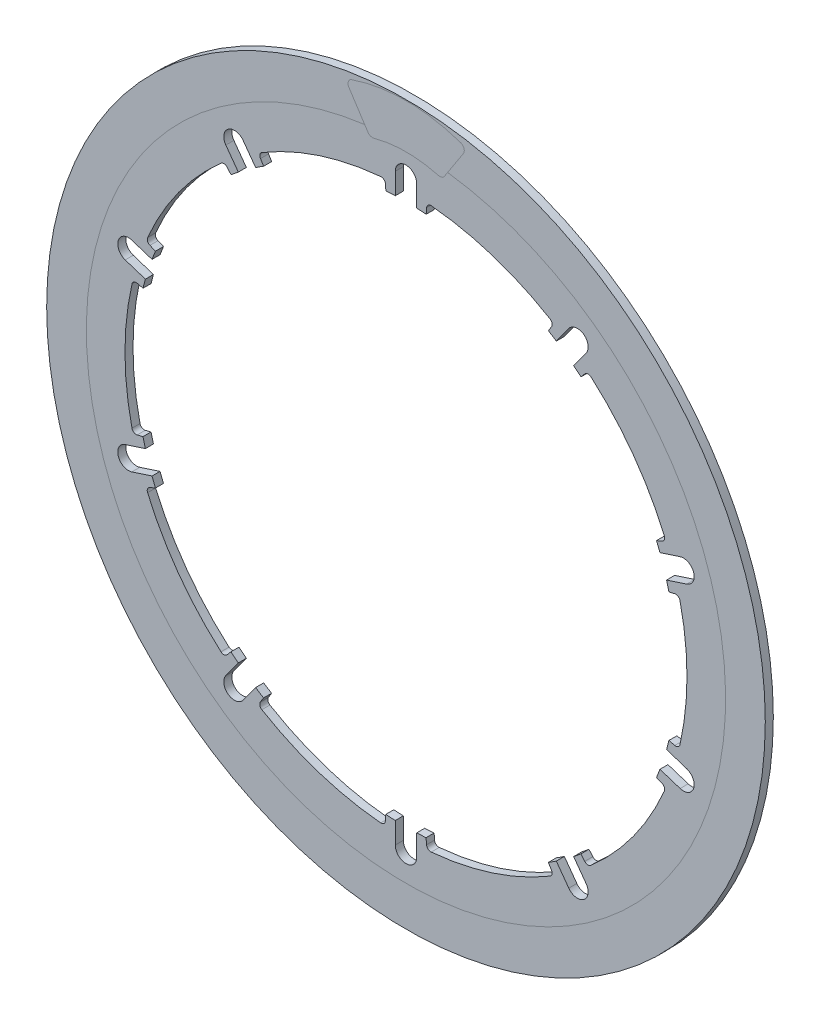
SolidWorks part; units mm, degrees
material "Gray Cast Iron"
ref_plane "Front Plane" through (0, 0, 0) normal (0, 0, 1) x (1, 0, 0)
ref_plane "Top Plane" through (0, 0, 0) normal (0, 1, 0) x (1, 0, 0)
ref_plane "Right Plane" through (0, 0, 0) normal (1, 0, 0) x (0, 0, -1)
sketch "Sketch1" plane through (0, 0, 0) normal (0, 0, 1) x (1, 0, 0)
  circle A0 centre (0, 0) radius 212.725
  dimension "D1" = 425.45
extrude "Boss-Extrude1" add sketch "Sketch1" along normal blind 4.7625
sketch3d "3DSketch3" [suppressed]
  line L4 (22.632, 184.3324, 30.7403) -> (33.9015, 201.686, 30.7403)
  line L5 (-33.9015, 201.686, 30.7403) -> (-22.632, 184.3324, 30.7403)
  arc A2 (-19.1346, 182.9983, 30.7403) -> (19.1346, 182.9983, 30.7403) centre (0, 112.7617, 30.7403) ccw
  spline S10 degree 3 poles (-22.632, 184.3324, 30.7403) (-22.5988, 184.2811, 30.7403) (-22.5293, 184.1805, 30.7403) (-22.4165, 184.0361, 30.7403) (-22.2957, 183.8983, 30.7403) (-22.1669, 183.7678, 30.7403) (-22.0309, 183.6449, 30.7403) (-21.8881, 183.53, 30.7403) (-21.7389, 183.4235, 30.7403) (-21.5838, 183.3258, 30.7403) (-21.4233, 183.2372, 30.7403) (-21.258, 183.1581, 30.7403) (-21.0428, 183.0698, 30.7403) (-20.7737, 182.9843, 30.7403) (-20.4488, 182.9172, 30.7403) (-20.1187, 182.8844, 30.7403) (-19.7871, 182.8865, 30.7403) (-19.4572, 182.9221, 30.7403) (-19.2411, 182.9691, 30.7403) (-19.1346, 182.9983, 30.7403) knots 0 0 0 0 0.045782 0.091558 0.137334 0.183113 0.228892 0.274672 0.32045 0.366227 0.412004 0.457782 0.503559 0.586301 0.669039 0.751777 0.834518 0.917255 1 1 1 1
  spline S11 degree 3 poles (19.1346, 182.9983, 30.7403) (19.1932, 182.9822, 30.7403) (19.3112, 182.9536, 30.7403) (19.4903, 182.9212, 30.7403) (19.6709, 182.8988, 30.7403) (19.8526, 182.8871, 30.7403) (20.0347, 182.8856, 30.7403) (20.2165, 182.8946, 30.7403) (20.3976, 182.9139, 30.7403) (20.5772, 182.9436, 30.7403) (20.7548, 182.9836, 30.7403) (20.9299, 183.0336, 30.7403) (21.1494, 183.1103, 30.7403) (21.4086, 183.2251, 30.7403) (21.6981, 183.3917, 30.7403) (21.9686, 183.5877, 30.7403) (22.2165, 183.8112, 30.7403) (22.4407, 184.059, 30.7403) (22.5716, 184.239, 30.7403) (22.632, 184.3324, 30.7403) knots 0 0 0 0 0.045473 0.090941 0.136409 0.181879 0.227351 0.272822 0.318291 0.36376 0.409229 0.454698 0.500168 0.583473 0.666777 0.750082 0.83339 0.916693 1 1 1 1
  spline S12 degree 3 poles (33.9015, 201.686, 30.7403) (33.9344, 201.7364, 30.7403) (33.9971, 201.839, 30.7403) (34.0817, 201.9976, 30.7403) (34.1575, 202.1609, 30.7403) (34.2237, 202.3283, 30.7403) (34.2804, 202.4992, 30.7403) (34.3274, 202.6731, 30.7403) (34.3646, 202.8492, 30.7403) (34.3917, 203.0273, 30.7403) (34.4086, 203.2065, 30.7403) (34.4153, 203.3864, 30.7403) (34.4119, 203.5665, 30.7403) (34.3756, 204.0435, 30.7403) (34.1614, 204.8075, 30.7403) (33.6821, 205.4852, 30.7403) (33.2752, 205.8566, 30.7403) (33.0454, 206.0314, 30.7403) (32.8006, 206.1843, 30.7403) (32.5436, 206.3149, 30.7403) (32.3643, 206.3858, 30.7403) (32.2732, 206.417, 30.7403) knots 0 0 0 0 0.031297 0.062588 0.093878 0.12517 0.156463 0.187756 0.219048 0.250339 0.28163 0.312921 0.344212 0.375504 0.562427 0.749344 0.799474 0.849606 0.899737 0.949865 1 1 1 1
  spline S13 degree 3 poles (32.2732, 206.417, 30.7403) (31.9592, 206.5252, 30.7403) (31.3303, 206.7384, 30.7403) (30.3838, 207.0486, 30.7403) (29.4343, 207.3495, 30.7403) (28.4817, 207.6406, 30.7403) (27.5262, 207.9222, 30.7403) (26.568, 208.1942, 30.7403) (25.6071, 208.4564, 30.7403) (24.6436, 208.7091, 30.7403) (23.6776, 208.952, 30.7403) (22.7092, 209.1852, 30.7403) (21.7385, 209.4087, 30.7403) (20.7656, 209.6224, 30.7403) (19.7906, 209.8263, 30.7403) (18.8136, 210.0204, 30.7403) (17.8348, 210.2046, 30.7403) (16.8541, 210.3791, 30.7403) (15.8717, 210.5436, 30.7403) (14.8877, 210.6982, 30.7403) (13.9022, 210.843, 30.7403) (12.9153, 210.9778, 30.7403) (11.927, 211.1027, 30.7403) (9.4532, 211.3901, 30.7403) (5.4798, 211.7206, 30.7403) (0, 211.8722, 30.7403) (-5.4798, 211.7206, 30.7403) (-9.7842, 211.3626, 30.7403) (-12.9159, 210.9828, 30.7403) (-14.8884, 210.7032, 30.7403) (-16.8549, 210.384, 30.7403) (-18.8146, 210.0253, 30.7403) (-20.7667, 209.6273, 30.7403) (-22.7103, 209.1901, 30.7403) (-24.6448, 208.7139, 30.7403) (-26.5694, 208.1991, 30.7403) (-28.483, 207.645, 30.7403) (-30.3853, 207.0535, 30.7403) (-31.6453, 206.6334, 30.7403) (-32.2732, 206.417, 30.7403) knots 0 0 0 0 0.015151 0.030302 0.045452 0.060603 0.075754 0.090905 0.106056 0.121206 0.136357 0.151508 0.166659 0.18181 0.19696 0.212111 0.227262 0.242413 0.257563 0.272714 0.287865 0.303016 0.318167 0.333317 0.41666 0.500002 0.583344 0.666687 0.696988 0.727289 0.75759 0.787892 0.818193 0.848494 0.878795 0.909096 0.939398 0.969699 1 1 1 1
  spline S14 degree 3 poles (-32.2732, 206.417, 30.7403) (-32.33, 206.3976, 30.7403) (-32.4424, 206.3554, 30.7403) (-32.6063, 206.2826, 30.7403) (-32.7663, 206.2007, 30.7403) (-32.9213, 206.1097, 30.7403) (-33.071, 206.0102, 30.7403) (-33.2148, 205.9024, 30.7403) (-33.3523, 205.7867, 30.7403) (-33.4831, 205.6634, 30.7403) (-33.6067, 205.5329, 30.7403) (-33.7226, 205.3956, 30.7403) (-33.8307, 205.2519, 30.7403) (-34.0967, 204.8533, 30.7403) (-34.3994, 204.1174, 30.7403) (-34.4385, 203.2861, 30.7403) (-34.346, 202.7423, 30.7403) (-34.2724, 202.4636, 30.7403) (-34.1736, 202.193, 30.7403) (-34.0515, 201.9325, 30.7403) (-33.9541, 201.7665, 30.7403) (-33.9015, 201.686, 30.7403) knots 0 0 0 0 0.031241 0.062476 0.093711 0.124947 0.156184 0.187421 0.218658 0.249893 0.281128 0.312363 0.343599 0.374835 0.562326 0.749809 0.799846 0.849885 0.899924 0.949958 1 1 1 1
  point P8 (0, 112.7617, -42.0561)
sketch "Sketch4" plane through (0, 0, 4.7625) normal (0, 0, 1) x (1, 0, 0)
  line L2 (22.7365, 184.6731) -> (34.006, 202.0267)
  line L3 (-33.7971, 202.0267) -> (-22.5275, 184.6731)
  arc A1 (19.2391, 183.339) -> (-19.0302, 183.339) centre (0.1045, 113.1023) ccw
  spline S5 degree 3 poles (34.006, 202.0267) (34.0389, 202.0771) (34.1016, 202.1797) (34.1862, 202.3383) (34.262, 202.5016) (34.3282, 202.669) (34.4038, 202.8969) (34.46, 203.1306) (34.4962, 203.3679) (34.5131, 203.5472) (34.5198, 203.7271) (34.5163, 203.9072) (34.4801, 204.3842) (34.2659, 205.1481) (33.7866, 205.8259) (33.3797, 206.1973) (33.1498, 206.3721) (32.9051, 206.525) (32.648, 206.6556) (32.4688, 206.7265) (32.3776, 206.7577) knots 0 0 0 0 0.031297 0.062588 0.093878 0.12517 0.156463 0.219048 0.250339 0.28163 0.312921 0.344212 0.375504 0.562427 0.749344 0.799474 0.849606 0.899737 0.949865 1 1 1 1
  spline S6 degree 3 poles (19.2391, 183.339) (19.2977, 183.3229) (19.4156, 183.2943) (19.5948, 183.2619) (19.7754, 183.2395) (19.9571, 183.2278) (20.1392, 183.2263) (20.321, 183.2353) (20.5021, 183.2546) (20.7416, 183.2942) (20.9771, 183.3543) (21.2539, 183.451) (21.5131, 183.5658) (21.8026, 183.7323) (22.073, 183.9284) (22.321, 184.1519) (22.5452, 184.3996) (22.6761, 184.5797) (22.7365, 184.6731) knots 0 0 0 0 0.045473 0.090941 0.136409 0.181879 0.227351 0.272822 0.318291 0.36376 0.454698 0.500168 0.583473 0.666777 0.750082 0.83339 0.916693 1 1 1 1
  spline S7 degree 3 poles (-22.5275, 184.6731) (-22.4943, 184.6218) (-22.4249, 184.5212) (-22.312, 184.3768) (-22.1912, 184.239) (-22.0624, 184.1085) (-21.9264, 183.9856) (-21.7836, 183.8707) (-21.6344, 183.7642) (-21.4276, 183.6339) (-21.2101, 183.5219) (-20.9383, 183.4105) (-20.6692, 183.325) (-20.3444, 183.2579) (-20.0142, 183.225) (-19.6827, 183.2272) (-19.3527, 183.2628) (-19.1367, 183.3098) (-19.0302, 183.339) knots 0 0 0 0 0.045782 0.091558 0.137334 0.183113 0.228892 0.274672 0.32045 0.366227 0.457782 0.503559 0.586301 0.669039 0.751777 0.834518 0.917255 1 1 1 1
  spline S8 degree 3 poles (-32.1687, 206.7577) (-32.2255, 206.7383) (-32.3379, 206.6961) (-32.5019, 206.6233) (-32.6618, 206.5414) (-32.8168, 206.4504) (-33.0164, 206.3177) (-33.2043, 206.1685) (-33.3786, 206.0041) (-33.5022, 205.8736) (-33.6182, 205.7363) (-33.7262, 205.5926) (-33.9922, 205.194) (-34.2949, 204.4581) (-34.3341, 203.6268) (-34.2415, 203.083) (-34.1679, 202.8043) (-34.0691, 202.5337) (-33.947, 202.2732) (-33.8496, 202.1072) (-33.7971, 202.0267) knots 0 0 0 0 0.031241 0.062476 0.093711 0.124947 0.156184 0.218658 0.249893 0.281128 0.312363 0.343599 0.374835 0.562326 0.749809 0.799846 0.849885 0.899924 0.949958 1 1 1 1
  spline S9 degree 3 poles (32.3776, 206.7577) (32.0637, 206.8659) (31.4348, 207.0791) (30.4883, 207.3893) (29.5388, 207.6902) (28.5862, 207.9813) (26.9938, 208.4506) (23.7904, 209.325) (20.2255, 210.1269) (16.6328, 210.7845) (14.6646, 211.0938) (13.0197, 211.3185) (12.0315, 211.4434) (9.5577, 211.7308) (5.5843, 212.0613) (0.1045, 212.2129) (-5.3753, 212.0613) (-9.6798, 211.7033) (-12.8114, 211.3235) (-14.7839, 211.0439) (-16.7504, 210.7247) (-18.7101, 210.366) (-20.6622, 209.968) (-22.6058, 209.5308) (-24.5403, 209.0546) (-26.4649, 208.5398) (-28.3785, 207.9857) (-30.2808, 207.3942) (-31.5409, 206.9741) (-32.1687, 206.7577) knots 0 0 0 0 0.015151 0.030302 0.045452 0.060603 0.075754 0.121206 0.212111 0.242413 0.287865 0.303016 0.318167 0.333317 0.41666 0.500002 0.583344 0.666687 0.696988 0.727289 0.75759 0.787892 0.818193 0.848494 0.878795 0.909096 0.939398 0.969699 1 1 1 1
sketch "Sketch8" plane through (0, 0, 0) normal (0, 0, -1) x (-1, 0, 0)
  circle A0 centre (0, 0) radius 166.37
  dimension "D1" = 332.74
extrude "Cut-Extrude1" cut sketch "Sketch8" against normal up to surface (4.7625 mm away) up to face at (212.725, 0, 4.7625)
sketch "Sketch9" plane through (0, 0, 0) normal (0, 0, -1) x (-1, 0, 0)
  line L1 (-6.35, 160.02) -> (6.35, 160.02)
  line L2 (-6.35, 160.02) -> (-6.35, 172.72)
  line L3 (-6.35, 172.72) -> (6.35, 172.72)
  line L4 (6.35, 160.02) -> (6.35, 172.72)
  line L5 (-6.35, 160.02) -> (6.35, 172.72) construction
  line L6 (-6.35, 172.72) -> (6.35, 160.02) construction
  circle A0 centre (0, 0) radius 166.37 construction
  circle A1 centre (0, 172.72) radius 6.35
  point P0 (0, 166.37)
  circle M4 centre (0, 0) radius 166.37
  dimension "D1" = 12.7
  dimension "D2" = 12.7
extrude "Cut-Extrude3" cut sketch "Sketch9" along direction (0, 0, 1) on the side against the normal up to surface (4.7625 mm away) contours L3 A1 | L3 A1 | A1 L4 M4 | A1 L2 M4
pattern_circular "CirPattern1" count 10 every 36 about axis through (0, 0, 0) along (0, 0, 1) of "Cut-Extrude3"
sketch "Sketch11" plane through (0, 0, 4.7625) normal (0, 0, 1) x (1, 0, 0)
  line L0 (-11.8938, 159.8321) -> (-12.1576, 163.3594)
  line L1 (-6.35, 166.2488) -> (-6.35, 160.1482)
  line L2 (6.35, 160.1482) -> (6.35, 166.2488)
  line L3 (11.9607, 159.8271) -> (12.2246, 163.3535)
  line L4 (6.35, 166.2488) -> (6.35, 172.72) construction
  arc A0 (11.9607, 159.8271) -> (6.35, 160.1482) centre (0, 0) ccw
  arc A1 (-6.35, 166.2488) -> (-92.5813, 138.2305) centre (0, 0) ccw construction
  arc A2 (92.5813, 138.2305) -> (6.35, 166.2488) centre (0, 0) ccw construction
  arc A3 (-6.35, 160.1482) -> (-11.8938, 159.8321) centre (0, 0) ccw
  arc A4 (-14.9183, 165.6998) -> (-92.5813, 138.2305) centre (0, 0) ccw
  arc A5 (92.5813, 138.2305) -> (14.9864, 165.6937) centre (0, 0) ccw
  arc A6 (-14.9183, 165.6998) -> (-12.1576, 163.3594) centre (-14.6905, 163.17) cw
  arc A7 (14.9864, 165.6937) -> (12.2246, 163.3535) centre (14.7576, 163.164) ccw
  arc M5 (-92.5813, 138.2305) -> (-6.35, 166.2488) centre (0, 0) cw
  arc M9 (6.35, 166.2488) -> (92.5813, 138.2305) centre (0, 0) cw
  dimension "D2" = 2.54
  dimension "D3" = 2.54
extrude "Boss-Extrude2" add sketch "Sketch11" against normal up to surface (4.7625 mm away) contours A0 L3 L2 M9 | A3 L1 L0 M5 up to face at (0, 0, 0)
pattern_circular "CirPattern2" count 10 every 36 about axis through (0, 0, 0) along (0, 0, 1) of "Boss-Extrude2"
sketch "Sketch15" [suppressed] plane through (0, 0, 6.35) normal (0, 0, 1) x (1, 0, 0)
  line L0 (-12.2165, 163.3739) -> (12.2261, 163.3732)
sketch "Sketch17" [suppressed] plane through (0, 0, 6.35) normal (0, 0, 1) x (1, 0, 0)
  line L0 (0, 0) -> (110.7699, 130.7089)
  line L1 (0, 0) -> (158.5451, 64.9479)
  arc A0 (161.9209, 73.4471) -> (119.8963, 131.2925) centre (0, 0) ccw
  arc A1 (161.9209, 73.4471) -> (158.5451, 64.9479) centre (156.138, 70.824) cw
  arc A2 (110.7699, 130.7089) -> (119.8963, 131.2925) centre (115.6143, 126.6035) cw
  dimension "D1" = 0
  dimension "D3" = 6.35
  dimension "D4" = 6.35
  dimension "D2" = 0
sketch "Sketch18" plane through (0, 0, 0) normal (0, 0, -1) x (-1, 0, 0)
  line L0 (33.7971, 202.0267) -> (22.5275, 184.6731) construction
  line L1 (-22.7365, 184.6731) -> (-34.006, 202.0267) construction
  line L2 (33.7971, 202.0267) -> (22.5275, 184.6731)
  line L3 (-22.7365, 184.6731) -> (-34.006, 202.0267)
  arc A0 (-24.6449, 187.6118) -> (24.4523, 187.637) centre (0, 0) ccw
  circle A1 centre (0, 0) radius 215.3351
  arc A2 (19.0302, 183.339) -> (-19.2391, 183.339) centre (-0.1045, 113.1023) ccw construction
  arc A3 (19.0302, 183.339) -> (-19.2391, 183.339) centre (-0.1045, 113.1023) ccw
  spline S0 degree 3 poles (-1450.1633, -1164.7301) (-59.0763, 285.4864) (32.2795, 197.129) (22.312, 184.3768) (22.1912, 184.239) (22.0624, 184.1085) (21.9264, 183.9856) (21.7836, 183.8707) (21.6344, 183.7642) (21.4276, 183.6339) (21.2101, 183.5219) (20.9383, 183.4105) (20.6692, 183.325) (20.3444, 183.2579) (20.0142, 183.225) (19.6827, 183.2272) (2.7527, 185.055) (8.5785, 322.4741) (2007.8128, 363.0309) knots -11.991769 -11.991769 -11.991769 -11.991769 0.045782 0.091558 0.137334 0.183113 0.228892 0.274672 0.32045 0.366227 0.457782 0.503559 0.586301 0.669039 0.751777 0.834518 0.917255 13.489507 13.489507 13.489507 13.489507 only from (22.5275, 184.6731) to (19.0302, 183.339) construction
  spline S1 degree 3 poles (-2016.3209, 153.4131) (-13.1774, 313.7756) (-3.6105, 186.1555) (-19.5948, 183.2619) (-19.7754, 183.2395) (-19.9571, 183.2278) (-20.1392, 183.2263) (-20.321, 183.2353) (-20.5021, 183.2546) (-20.7416, 183.2942) (-20.9771, 183.3543) (-21.2539, 183.451) (-21.5131, 183.5658) (-21.8026, 183.7323) (-22.073, 183.9284) (-22.321, 184.1519) (-33.7349, 196.7661) (61.8944, 295.2324) (1583.0626, -1002.353) knots -12.036429 -12.036429 -12.036429 -12.036429 0.045473 0.090941 0.136409 0.181879 0.227351 0.272822 0.318291 0.36376 0.454698 0.500168 0.583473 0.666777 0.750082 0.83339 0.916693 13.47468 13.47468 13.47468 13.47468 only from (-19.2391, 183.339) to (-22.7365, 184.6731) construction
  spline S2 degree 3 poles (-741.6985, 2071.3636) (51.5513, 215.3428) (-28.083, 190.8965) (-34.1862, 202.3383) (-34.262, 202.5016) (-34.3282, 202.669) (-34.4038, 202.8969) (-34.46, 203.1306) (-34.4962, 203.3679) (-34.5131, 203.5472) (-34.5198, 203.7271) (-34.5163, 203.9072) (-34.4801, 204.3842) (-34.2659, 205.1481) (-33.7866, 205.8259) (-33.3797, 206.1973) (-33.1498, 206.3721) (-32.9051, 206.525) (-19.4783, 213.3465) (41.9008, 122.514) (-1615.5521, -1012.0405) knots -6.679954 -6.679954 -6.679954 -6.679954 0.031297 0.062588 0.093878 0.12517 0.156463 0.219048 0.250339 0.28163 0.312921 0.344212 0.375504 0.562427 0.749344 0.799474 0.849606 0.899737 0.949865 8.706653 8.706653 8.706653 8.706653 only from (-34.006, 202.0267) to (-32.3776, 206.7577) construction
  spline S3 degree 3 poles (1661.243, 1259.3746) (-203.7859, -162.5293) (-163.0238, 163.9576) (-30.4883, 207.3893) (-29.5388, 207.6902) (-28.5862, 207.9813) (-26.9938, 208.4506) (-23.7904, 209.325) (-20.2255, 210.1269) (-16.6328, 210.7845) (-14.6646, 211.0938) (-13.0197, 211.3185) (-12.0315, 211.4434) (-9.5577, 211.7308) (-5.5843, 212.0613) (-0.1045, 212.2129) (5.3753, 212.0613) (9.6798, 211.7033) (12.8114, 211.3235) (14.7839, 211.0439) (16.7504, 210.7247) (18.7101, 210.366) (20.6622, 209.968) (22.6058, 209.5308) (24.5403, 209.0546) (26.4649, 208.5398) (28.3785, 207.9857) (189.3327, 157.9434) (218.1983, -304.2931) (-1891.4217, 643.6889) knots -6.319065 -6.319065 -6.319065 -6.319065 0.015151 0.030302 0.045452 0.060603 0.075754 0.121206 0.212111 0.242413 0.287865 0.303016 0.318167 0.333317 0.41666 0.500002 0.583344 0.666687 0.696988 0.727289 0.75759 0.787892 0.818193 0.848494 0.878795 0.909096 0.939398 0.969699 8.600273 8.600273 8.600273 8.600273 only from (-32.3776, 206.7577) to (32.1687, 206.7577) construction
  spline S4 degree 3 poles (1741.3262, -829.6052) (-26.9574, 143.7974) (20.6648, 211.8759) (32.5019, 206.6233) (32.6618, 206.5414) (32.8168, 206.4504) (33.0164, 206.3177) (33.2043, 206.1685) (33.3786, 206.0041) (33.5022, 205.8736) (33.6182, 205.7363) (33.7262, 205.5926) (33.9922, 205.194) (34.2949, 204.4581) (34.3341, 203.6268) (34.2415, 203.083) (34.1679, 202.8043) (34.0691, 202.5337) (27.687, 188.9067) (-76.4304, 222.6453) (533.1826, 2136.6237) knots -6.671073 -6.671073 -6.671073 -6.671073 0.031241 0.062476 0.093711 0.124947 0.156184 0.218658 0.249893 0.281128 0.312363 0.343599 0.374835 0.562326 0.749809 0.799846 0.849885 0.899924 0.949958 8.70048 8.70048 8.70048 8.70048 only from (32.1687, 206.7577) to (33.7971, 202.0267) construction
  spline S5 degree 3 poles (22.5275, 184.6731) (22.4943, 184.6218) (22.4249, 184.5212) (22.312, 184.3768) (22.1912, 184.239) (22.0624, 184.1085) (21.9264, 183.9856) (21.7836, 183.8707) (21.6344, 183.7642) (21.4276, 183.6339) (21.2101, 183.5219) (20.9383, 183.4105) (20.6692, 183.325) (20.3444, 183.2579) (20.0142, 183.225) (19.6827, 183.2272) (19.3527, 183.2628) (19.1367, 183.3098) (19.0302, 183.339) knots 0 0 0 0 0.045782 0.091558 0.137334 0.183113 0.228892 0.274672 0.32045 0.366227 0.457782 0.503559 0.586301 0.669039 0.751777 0.834518 0.917255 1 1 1 1
  spline S6 degree 3 poles (-19.2391, 183.339) (-19.2977, 183.3229) (-19.4156, 183.2943) (-19.5948, 183.2619) (-19.7754, 183.2395) (-19.9571, 183.2278) (-20.1392, 183.2263) (-20.321, 183.2353) (-20.5021, 183.2546) (-20.7416, 183.2942) (-20.9771, 183.3543) (-21.2539, 183.451) (-21.5131, 183.5658) (-21.8026, 183.7323) (-22.073, 183.9284) (-22.321, 184.1519) (-22.5452, 184.3996) (-22.6761, 184.5797) (-22.7365, 184.6731) knots 0 0 0 0 0.045473 0.090941 0.136409 0.181879 0.227351 0.272822 0.318291 0.36376 0.454698 0.500168 0.583473 0.666777 0.750082 0.83339 0.916693 1 1 1 1
  spline S7 degree 3 poles (-34.006, 202.0267) (-34.0389, 202.0771) (-34.1016, 202.1797) (-34.1862, 202.3383) (-34.262, 202.5016) (-34.3282, 202.669) (-34.4038, 202.8969) (-34.46, 203.1306) (-34.4962, 203.3679) (-34.5131, 203.5472) (-34.5198, 203.7271) (-34.5163, 203.9072) (-34.4801, 204.3842) (-34.2659, 205.1481) (-33.7866, 205.8259) (-33.3797, 206.1973) (-33.1498, 206.3721) (-32.9051, 206.525) (-32.648, 206.6556) (-32.4688, 206.7265) (-32.3776, 206.7577) knots 0 0 0 0 0.031297 0.062588 0.093878 0.12517 0.156463 0.219048 0.250339 0.28163 0.312921 0.344212 0.375504 0.562427 0.749344 0.799474 0.849606 0.899737 0.949865 1 1 1 1
  spline S8 degree 3 poles (-32.3776, 206.7577) (-32.0637, 206.8659) (-31.4348, 207.0791) (-30.4883, 207.3893) (-29.5388, 207.6902) (-28.5862, 207.9813) (-26.9938, 208.4506) (-23.7904, 209.325) (-20.2255, 210.1269) (-16.6328, 210.7845) (-14.6646, 211.0938) (-13.0197, 211.3185) (-12.0315, 211.4434) (-9.5577, 211.7308) (-5.5843, 212.0613) (-0.1045, 212.2129) (5.3753, 212.0613) (9.6798, 211.7033) (12.8114, 211.3235) (14.7839, 211.0439) (16.7504, 210.7247) (18.7101, 210.366) (20.6622, 209.968) (22.6058, 209.5308) (24.5403, 209.0546) (26.4649, 208.5398) (28.3785, 207.9857) (30.2808, 207.3942) (31.5409, 206.9741) (32.1687, 206.7577) knots 0 0 0 0 0.015151 0.030302 0.045452 0.060603 0.075754 0.121206 0.212111 0.242413 0.287865 0.303016 0.318167 0.333317 0.41666 0.500002 0.583344 0.666687 0.696988 0.727289 0.75759 0.787892 0.818193 0.848494 0.878795 0.909096 0.939398 0.969699 1 1 1 1
  spline S9 degree 3 poles (32.1687, 206.7577) (32.2255, 206.7383) (32.3379, 206.6961) (32.5019, 206.6233) (32.6618, 206.5414) (32.8168, 206.4504) (33.0164, 206.3177) (33.2043, 206.1685) (33.3786, 206.0041) (33.5022, 205.8736) (33.6182, 205.7363) (33.7262, 205.5926) (33.9922, 205.194) (34.2949, 204.4581) (34.3341, 203.6268) (34.2415, 203.083) (34.1679, 202.8043) (34.0691, 202.5337) (33.947, 202.2732) (33.8496, 202.1072) (33.7971, 202.0267) knots 0 0 0 0 0.031241 0.062476 0.093711 0.124947 0.156184 0.218658 0.249893 0.281128 0.312363 0.343599 0.374835 0.562326 0.749809 0.799846 0.849885 0.899924 0.949958 1 1 1 1
  dimension "D1" = 378.4471
  dimension "D2" = 430.6702
split line "Split Line3"
sketch "Sketch19" plane through (0, 0, 6.35) normal (0, 0, 1) x (1, 0, 0)
  line L0 (-33.7971, 202.0267) -> (-22.5275, 184.6731) construction
  line L1 (22.7365, 184.6731) -> (34.006, 202.0267) construction
  line L2 (-33.7971, 202.0267) -> (-22.5275, 184.6731)
  line L3 (22.7365, 184.6731) -> (34.006, 202.0267)
  arc A0 (-24.4523, 187.637) -> (24.6449, 187.6118) centre (0, 0) ccw
  circle A1 centre (0, 0) radius 215.3351
  arc A2 (19.2391, 183.339) -> (-19.0302, 183.339) centre (0.1045, 113.1023) ccw construction
  arc A3 (19.2391, 183.339) -> (-19.0302, 183.339) centre (0.1045, 113.1023) ccw
  spline S0 degree 3 poles (1450.1633, -1164.7301) (59.0763, 285.4864) (-32.2795, 197.129) (-22.312, 184.3768) (-22.1912, 184.239) (-22.0624, 184.1085) (-21.9264, 183.9856) (-21.7836, 183.8707) (-21.6344, 183.7642) (-21.4276, 183.6339) (-21.2101, 183.5219) (-20.9383, 183.4105) (-20.6692, 183.325) (-20.3444, 183.2579) (-20.0142, 183.225) (-19.6827, 183.2272) (-2.7527, 185.055) (-8.5785, 322.4741) (-2007.8128, 363.0309) knots -11.991769 -11.991769 -11.991769 -11.991769 0.045782 0.091558 0.137334 0.183113 0.228892 0.274672 0.32045 0.366227 0.457782 0.503559 0.586301 0.669039 0.751777 0.834518 0.917255 13.489507 13.489507 13.489507 13.489507 only from (-22.5275, 184.6731) to (-19.0302, 183.339) construction
  spline S1 degree 3 poles (-1741.3262, -829.6052) (26.9574, 143.7974) (-20.6648, 211.8759) (-32.5019, 206.6233) (-32.6618, 206.5414) (-32.8168, 206.4504) (-33.0164, 206.3177) (-33.2043, 206.1685) (-33.3786, 206.0041) (-33.5022, 205.8736) (-33.6182, 205.7363) (-33.7262, 205.5926) (-33.9922, 205.194) (-34.2949, 204.4581) (-34.3341, 203.6268) (-34.2415, 203.083) (-34.1679, 202.8043) (-34.0691, 202.5337) (-27.687, 188.9067) (76.4304, 222.6453) (-533.1826, 2136.6237) knots -6.671073 -6.671073 -6.671073 -6.671073 0.031241 0.062476 0.093711 0.124947 0.156184 0.218658 0.249893 0.281128 0.312363 0.343599 0.374835 0.562326 0.749809 0.799846 0.849885 0.899924 0.949958 8.70048 8.70048 8.70048 8.70048 only from (-32.1687, 206.7577) to (-33.7971, 202.0267) construction
  spline S2 degree 3 poles (-1661.243, 1259.3746) (203.7859, -162.5293) (163.0238, 163.9576) (30.4883, 207.3893) (29.5388, 207.6902) (28.5862, 207.9813) (26.9938, 208.4506) (23.7904, 209.325) (20.2255, 210.1269) (16.6328, 210.7845) (14.6646, 211.0938) (13.0197, 211.3185) (12.0315, 211.4434) (9.5577, 211.7308) (5.5843, 212.0613) (0.1045, 212.2129) (-5.3753, 212.0613) (-9.6798, 211.7033) (-12.8114, 211.3235) (-14.7839, 211.0439) (-16.7504, 210.7247) (-18.7101, 210.366) (-20.6622, 209.968) (-22.6058, 209.5308) (-24.5403, 209.0546) (-26.4649, 208.5398) (-28.3785, 207.9857) (-189.3327, 157.9434) (-218.1983, -304.2931) (1891.4217, 643.6889) knots -6.319065 -6.319065 -6.319065 -6.319065 0.015151 0.030302 0.045452 0.060603 0.075754 0.121206 0.212111 0.242413 0.287865 0.303016 0.318167 0.333317 0.41666 0.500002 0.583344 0.666687 0.696988 0.727289 0.75759 0.787892 0.818193 0.848494 0.878795 0.909096 0.939398 0.969699 8.600273 8.600273 8.600273 8.600273 only from (32.3776, 206.7577) to (-32.1687, 206.7577) construction
  spline S3 degree 3 poles (741.6985, 2071.3636) (-51.5513, 215.3428) (28.083, 190.8965) (34.1862, 202.3383) (34.262, 202.5016) (34.3282, 202.669) (34.4038, 202.8969) (34.46, 203.1306) (34.4962, 203.3679) (34.5131, 203.5472) (34.5198, 203.7271) (34.5163, 203.9072) (34.4801, 204.3842) (34.2659, 205.1481) (33.7866, 205.8259) (33.3797, 206.1973) (33.1498, 206.3721) (32.9051, 206.525) (19.4783, 213.3465) (-41.9008, 122.514) (1615.5521, -1012.0405) knots -6.679954 -6.679954 -6.679954 -6.679954 0.031297 0.062588 0.093878 0.12517 0.156463 0.219048 0.250339 0.28163 0.312921 0.344212 0.375504 0.562427 0.749344 0.799474 0.849606 0.899737 0.949865 8.706653 8.706653 8.706653 8.706653 only from (34.006, 202.0267) to (32.3776, 206.7577) construction
  spline S4 degree 3 poles (2016.3209, 153.4131) (13.1774, 313.7756) (3.6105, 186.1555) (19.5948, 183.2619) (19.7754, 183.2395) (19.9571, 183.2278) (20.1392, 183.2263) (20.321, 183.2353) (20.5021, 183.2546) (20.7416, 183.2942) (20.9771, 183.3543) (21.2539, 183.451) (21.5131, 183.5658) (21.8026, 183.7323) (22.073, 183.9284) (22.321, 184.1519) (33.7349, 196.7661) (-61.8944, 295.2324) (-1583.0626, -1002.353) knots -12.036429 -12.036429 -12.036429 -12.036429 0.045473 0.090941 0.136409 0.181879 0.227351 0.272822 0.318291 0.36376 0.454698 0.500168 0.583473 0.666777 0.750082 0.83339 0.916693 13.47468 13.47468 13.47468 13.47468 only from (19.2391, 183.339) to (22.7365, 184.6731) construction
  spline S5 degree 3 poles (-22.5275, 184.6731) (-22.4943, 184.6218) (-22.4249, 184.5212) (-22.312, 184.3768) (-22.1912, 184.239) (-22.0624, 184.1085) (-21.9264, 183.9856) (-21.7836, 183.8707) (-21.6344, 183.7642) (-21.4276, 183.6339) (-21.2101, 183.5219) (-20.9383, 183.4105) (-20.6692, 183.325) (-20.3444, 183.2579) (-20.0142, 183.225) (-19.6827, 183.2272) (-19.3527, 183.2628) (-19.1367, 183.3098) (-19.0302, 183.339) knots 0 0 0 0 0.045782 0.091558 0.137334 0.183113 0.228892 0.274672 0.32045 0.366227 0.457782 0.503559 0.586301 0.669039 0.751777 0.834518 0.917255 1 1 1 1
  spline S6 degree 3 poles (-32.1687, 206.7577) (-32.2255, 206.7383) (-32.3379, 206.6961) (-32.5019, 206.6233) (-32.6618, 206.5414) (-32.8168, 206.4504) (-33.0164, 206.3177) (-33.2043, 206.1685) (-33.3786, 206.0041) (-33.5022, 205.8736) (-33.6182, 205.7363) (-33.7262, 205.5926) (-33.9922, 205.194) (-34.2949, 204.4581) (-34.3341, 203.6268) (-34.2415, 203.083) (-34.1679, 202.8043) (-34.0691, 202.5337) (-33.947, 202.2732) (-33.8496, 202.1072) (-33.7971, 202.0267) knots 0 0 0 0 0.031241 0.062476 0.093711 0.124947 0.156184 0.218658 0.249893 0.281128 0.312363 0.343599 0.374835 0.562326 0.749809 0.799846 0.849885 0.899924 0.949958 1 1 1 1
  spline S7 degree 3 poles (32.3776, 206.7577) (32.0637, 206.8659) (31.4348, 207.0791) (30.4883, 207.3893) (29.5388, 207.6902) (28.5862, 207.9813) (26.9938, 208.4506) (23.7904, 209.325) (20.2255, 210.1269) (16.6328, 210.7845) (14.6646, 211.0938) (13.0197, 211.3185) (12.0315, 211.4434) (9.5577, 211.7308) (5.5843, 212.0613) (0.1045, 212.2129) (-5.3753, 212.0613) (-9.6798, 211.7033) (-12.8114, 211.3235) (-14.7839, 211.0439) (-16.7504, 210.7247) (-18.7101, 210.366) (-20.6622, 209.968) (-22.6058, 209.5308) (-24.5403, 209.0546) (-26.4649, 208.5398) (-28.3785, 207.9857) (-30.2808, 207.3942) (-31.5409, 206.9741) (-32.1687, 206.7577) knots 0 0 0 0 0.015151 0.030302 0.045452 0.060603 0.075754 0.121206 0.212111 0.242413 0.287865 0.303016 0.318167 0.333317 0.41666 0.500002 0.583344 0.666687 0.696988 0.727289 0.75759 0.787892 0.818193 0.848494 0.878795 0.909096 0.939398 0.969699 1 1 1 1
  spline S8 degree 3 poles (34.006, 202.0267) (34.0389, 202.0771) (34.1016, 202.1797) (34.1862, 202.3383) (34.262, 202.5016) (34.3282, 202.669) (34.4038, 202.8969) (34.46, 203.1306) (34.4962, 203.3679) (34.5131, 203.5472) (34.5198, 203.7271) (34.5163, 203.9072) (34.4801, 204.3842) (34.2659, 205.1481) (33.7866, 205.8259) (33.3797, 206.1973) (33.1498, 206.3721) (32.9051, 206.525) (32.648, 206.6556) (32.4688, 206.7265) (32.3776, 206.7577) knots 0 0 0 0 0.031297 0.062588 0.093878 0.12517 0.156463 0.219048 0.250339 0.28163 0.312921 0.344212 0.375504 0.562427 0.749344 0.799474 0.849606 0.899737 0.949865 1 1 1 1
  spline S9 degree 3 poles (19.2391, 183.339) (19.2977, 183.3229) (19.4156, 183.2943) (19.5948, 183.2619) (19.7754, 183.2395) (19.9571, 183.2278) (20.1392, 183.2263) (20.321, 183.2353) (20.5021, 183.2546) (20.7416, 183.2942) (20.9771, 183.3543) (21.2539, 183.451) (21.5131, 183.5658) (21.8026, 183.7323) (22.073, 183.9284) (22.321, 184.1519) (22.5452, 184.3996) (22.6761, 184.5797) (22.7365, 184.6731) knots 0 0 0 0 0.045473 0.090941 0.136409 0.181879 0.227351 0.272822 0.318291 0.36376 0.454698 0.500168 0.583473 0.666777 0.750082 0.83339 0.916693 1 1 1 1
  dimension "D1" = 378.4471
  dimension "D2" = 430.6702
split line "Split Line4"
sketch "Sketch20" plane through (0, 0, 0) normal (0, 0, -1) x (-1, 0, 0)
  line L1 (-3.8126, 161.2345) -> (3.8319, 161.2345)
  line L2 (-3.8126, 161.2345) -> (-3.8126, 169.2274)
  line L3 (-3.8126, 169.2274) -> (-0.9809, 169.2274)
  line L4 (3.8319, 161.2345) -> (3.8319, 169.2274)
  line L5 (1.2675, 169.2274) -> (3.8319, 169.2274)
  line L7 (-0.9809, 169.2274) -> (-0.9809, 180.1204)
  line L8 (-0.9809, 180.1204) -> (1.2675, 180.1204)
  line L9 (1.2675, 169.2274) -> (1.2675, 180.1204)
  circle A0 centre (0, 165.1) radius 3.175
  dimension "D1" = 6.35
  dimension "D2" = 165.1
extrude "Boss-Extrude3" [suppressed] add sketch "Sketch20" against normal blind 0.0254
pattern_circular "CirPattern3" [suppressed] count 10 over 360
